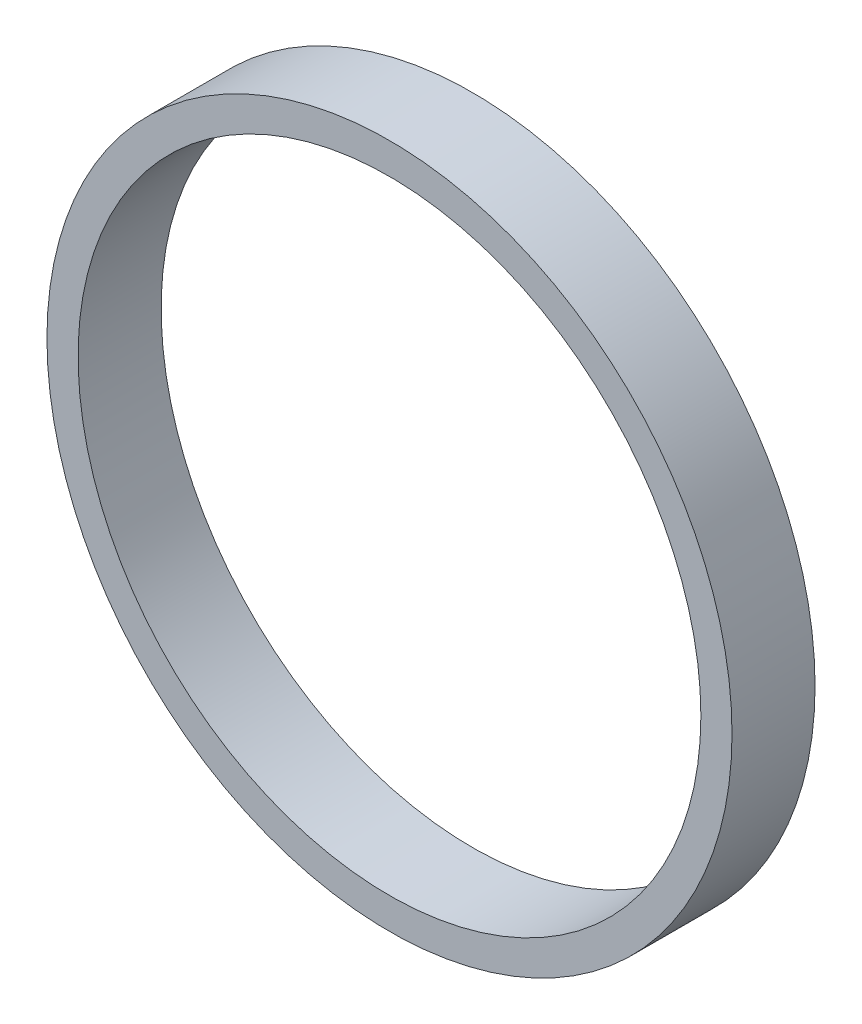
SolidWorks part; units mm, degrees
ref_plane "Front Plane" through (0, 0, 0) normal (0, 0, 1) x (1, 0, 0)
ref_plane "Top Plane" through (0, 0, 0) normal (0, 1, 0) x (1, 0, 0)
ref_plane "Right Plane" through (0, 0, 0) normal (1, 0, 0) x (0, 0, -1)
sketch "Sketch1" plane through (0, 0, 0) normal (0, 0, 1) x (1, 0, 0)
  circle A0 centre (0, 0) radius 15
  circle A1 centre (0, 0) radius 16.5
  dimension "D1" = 33
  dimension "D2" = 30
extrude "Boss-Extrude1" add sketch "Sketch1" along normal blind 4
